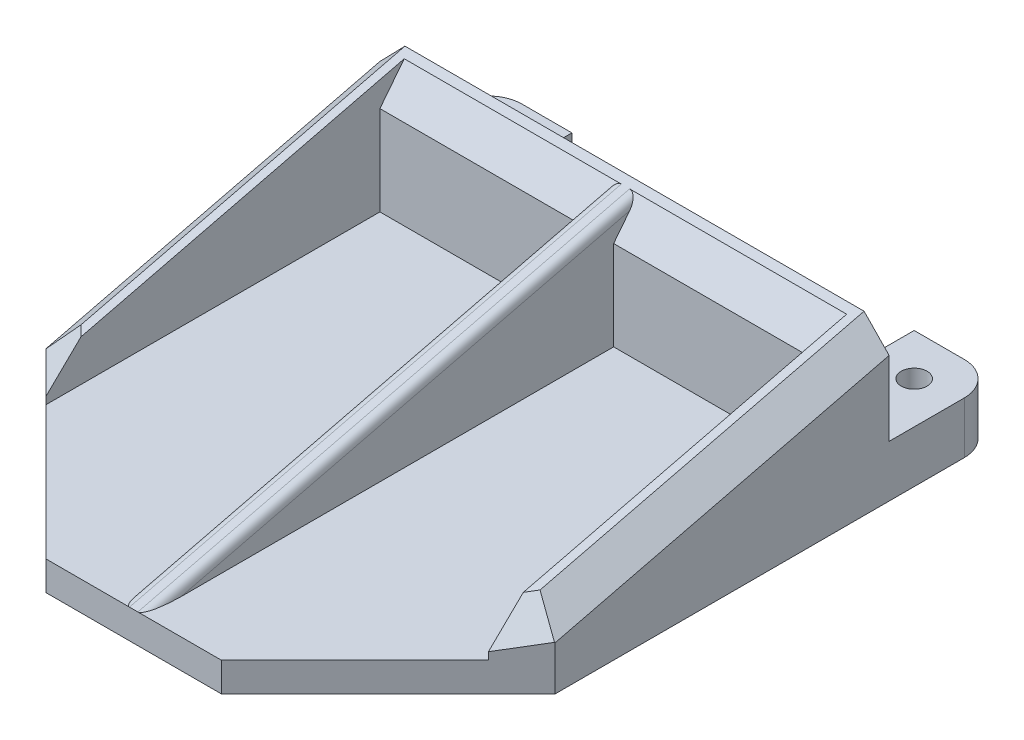
SolidWorks part; units mm, degrees
ref_plane "Front Plane" through (0, 0, 0) normal (0, 0, 1) x (1, 0, 0)
ref_plane "Top Plane" through (0, 0, 0) normal (0, 1, 0) x (1, 0, 0)
ref_plane "Right Plane" through (0, 0, 0) normal (1, 0, 0) x (0, 0, -1)
sketch "Sketch1" plane through (0, 0, 0) normal (0, 1, 0) x (1, 0, 0)
  line L0 (30.5, -11.5) -> (10.5, -31.5)
  line L1 (30.5, 31.5) -> (-30.5, 31.5)
  line L2 (30.5, 31.5) -> (30.5, -11.5)
  line L3 (10.5, -31.5) -> (-10.5, -31.5)
  line L4 (-30.5, 31.5) -> (-30.5, -11.5)
  line L5 (30.5, 31.5) -> (-30.5, -31.5) construction
  line L6 (30.5, -31.5) -> (-30.5, 31.5) construction
  line L7 (-10.5, -31.5) -> (-30.5, -11.5)
  line L8 (0, 31.5) -> (0, -31.5) construction
  line L9 (-30.5, 31.5) -> (-20.5, 31.5)
  line L10 (-30.5, 31.5) -> (-30.5, 37.5)
  line L11 (-26.5, 41.5) -> (-20.5, 41.5)
  line L12 (-20.5, 31.5) -> (-20.5, 41.5)
  line L14 (30.5, 31.5) -> (20.5, 31.5)
  line L15 (30.5, 31.5) -> (30.5, 37.5)
  line L16 (26.5, 41.5) -> (20.5, 41.5)
  line L17 (20.5, 31.5) -> (20.5, 41.5)
  arc A0 (-30.5, 37.5) -> (-26.5, 41.5) centre (-26.5, 37.5) cw
  circle A1 centre (-25.5, 36.5) radius 1.55
  arc A2 (30.5, 37.5) -> (26.5, 41.5) centre (26.5, 37.5) ccw
  circle A3 centre (25.5, 36.5) radius 1.55
  point P0 (0, 0)
  dimension "D7" = 4
  dimension "D10" = 3.1
  dimension "D13" = 4
  dimension "D14" = 3.1
  dimension "D1" = 61
  dimension "D2" = 63
  dimension "D3" = 10
  dimension "D4" = 10
  dimension "D8" = 5
  dimension "D9" = 5
  dimension "D11" = 10
  dimension "D12" = 10
  dimension "D15" = 5
  dimension "D16" = 5
extrude "Boss-Extrude1" add sketch "Sketch1" along normal mid plane 3.5 contours L7 L3 L0 L2 L1 L4 | L15 A2 L16 L17 L1 A3 | A0 L10 L1 L12 L11 A1
sketch "Sketch2" plane through (0, 1.75, 0) normal (0, 1, 0) x (1, 0, 0)
  line L0 (-30.5, 37.5) -> (-30.5, -11.5) construction
  line L1 (-20.5, 41.5) -> (-30.5, 41.5)
  line L2 (-20.5, 41.5) -> (-20.5, 31.5)
  line L3 (-20.5, 31.5) -> (-30.5, 31.5)
  line L4 (-30.5, 41.5) -> (-30.5, 31.5)
  line L5 (30.5, 37.5) -> (30.5, -11.5) construction
  line L6 (20.5, 41.5) -> (30.5, 41.5)
  line L7 (20.5, 41.5) -> (20.5, 31.5)
  line L8 (20.5, 31.5) -> (30.5, 31.5)
  line L9 (30.5, 41.5) -> (30.5, 31.5)
  line L11 (-30.5, 31.5) -> (30.5, 31.5)
  line L12 (-30.5, 31.5) -> (-30.5, 28.5)
  line L13 (-30.5, 28.5) -> (30.5, 28.5)
  line L14 (30.5, 31.5) -> (30.5, 28.5)
  circle A0 centre (-25.5, 36.5) radius 1.55
  circle A1 centre (25.5, 36.5) radius 1.55
  line M13 (30.5, -11.5) -> (30.5, 37.5)
  arc M14 (30.5, 37.5) -> (26.5, 41.5) centre (26.5, 37.5) ccw
  line M15 (26.5, 41.5) -> (20.5, 41.5)
  line M16 (20.5, 41.5) -> (20.5, 31.5)
  line M17 (20.5, 31.5) -> (-20.5, 31.5)
  line M18 (-20.5, 31.5) -> (-20.5, 41.5)
  line M19 (-20.5, 41.5) -> (-26.5, 41.5)
  arc M20 (-26.5, 41.5) -> (-30.5, 37.5) centre (-26.5, 37.5) ccw
  line M21 (-30.5, 37.5) -> (-30.5, -11.5)
  circle M22 centre (-25.5, 36.5) radius 1.55
  circle M23 centre (25.5, 36.5) radius 1.55
  dimension "D1" = 3.1
  dimension "D2" = 3.1
  dimension "D3" = 3
extrude "Boss-Extrude2" add sketch "Sketch2" along normal blind 2.7 contours L3 M18 M19 M20 M21 M22 | L13 L8 L3 M21 M13 M17 | L8 M16 M13 M14 M15 M23
sketch "Sketch3" plane through (0, 0, 0) normal (1, 0, 0) x (0, 0, -1)
  line L1 (28.5, 1.75) -> (-31.5, 1.75)
  line L2 (28.5, 1.75) -> (28.5, 16.45)
  line L5 (-31.5, 1.75) -> (28.5, 16.45)
  line L9 (28.5, 4.45) -> (37.5, 4.45) construction
  dimension "D1" = 60
  dimension "D2" = 12
extrude "Boss-Extrude3" add sketch "Sketch3" along normal blind 30.5 and the other way blind 30.5
ref_plane "Plane1" through (0, 16.45, 0) normal (0, -1, 0) x (-1, 0, 0)
sketch "Sketch4" plane through (0, 16.45, 0) normal (0, -1, 0) x (-1, 0, 0)
  line L0 (30.5, 28.5) -> (30.5, -31.5) construction
  line L1 (26.5, 24.5) -> (1.5, 24.5)
  line L2 (26.5, 24.5) -> (26.5, -31.5)
  line L3 (26.5, -31.5) -> (1.5, -31.5)
  line L4 (1.5, 24.5) -> (1.5, -31.5)
  line L5 (30.5, 28.5) -> (-30.5, 28.5) construction
  line L6 (30.5, -31.5) -> (10.5, -31.5) construction
  line L7 (0, 28.5) -> (0, -34.2923) construction
  line L8 (-26.5, -31.5) -> (-1.5, -31.5)
  line L9 (-1.5, 24.5) -> (-1.5, -31.5)
  line L10 (-26.5, 24.5) -> (-1.5, 24.5)
  line L11 (-26.5, 24.5) -> (-26.5, -31.5)
  line L12 (30.5, -11.5) -> (10.5, -31.5)
  line L13 (10.5, -31.5) -> (30.5, -31.5)
  line L14 (30.5, -31.5) -> (30.5, -11.5)
  line L15 (-10.5, -31.5) -> (-30.5, -11.5)
  line L16 (-30.5, -11.5) -> (-30.5, -31.5)
  line L17 (-30.5, -31.5) -> (-10.5, -31.5)
  dimension "D1" = 4
  dimension "D2" = 4
  dimension "D3" = 0
  dimension "D4" = 25
  dimension "D5" = 62.7923
extrude "Cut-Extrude1" cut sketch "Sketch4" along normal blind 14.7 contours L12 L2 L1 L4 L3 | L15 L8 L9 L10 L11 | L2 L12 L3 | L13 L14 L12 L2 | L8 L15 L11 | L16 L17 L11 L15
chamfer "Chamfer2" distance 3 6 edges at (28.5, 6.16, 13.5) (-28.5, 6.16, 13.5) (30.5, 11.55, -8.5) (14, 15.47, -24.5) (-14, 15.47, -24.5) (-30.5, 11.55, -8.5)
fillet "Fillet2" radius 1 2 edges at (1.5, 8.9669, 2.0431) (-1.5, 8.9669, 2.0431)
